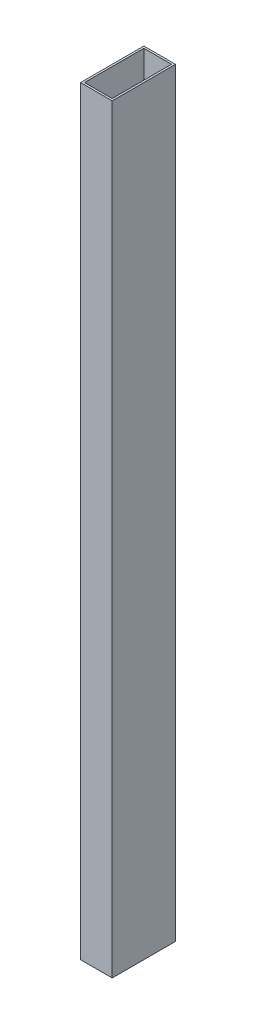
SolidWorks part; units mm, degrees
ref_plane "Front Plane" through (0, 0, 0) normal (0, 0, 1) x (1, 0, 0)
ref_plane "Top Plane" through (0, 0, 0) normal (0, 1, 0) x (1, 0, 0)
ref_plane "Right Plane" through (0, 0, 0) normal (1, 0, 0) x (0, 0, -1)
sketch "Sketch1" plane through (0, 0, 0) normal (0, 1, 0) x (1, 0, 0)
  line L1 (12.7, -25.4) -> (-12.7, -25.4)
  line L2 (12.7, -25.4) -> (12.7, 25.4)
  line L3 (12.7, 25.4) -> (-12.7, 25.4)
  line L4 (-12.7, -25.4) -> (-12.7, 25.4)
  line L5 (12.7, -25.4) -> (-12.7, 25.4) construction
  line L6 (12.7, 25.4) -> (-12.7, -25.4) construction
  line L7 (11.1125, -23.8125) -> (-11.1125, -23.8125)
  line L8 (11.1125, -23.8125) -> (11.1125, 23.8125)
  line L9 (11.1125, 23.8125) -> (-11.1125, 23.8125)
  line L10 (-11.1125, -23.8125) -> (-11.1125, 23.8125)
  line L11 (11.1125, -23.8125) -> (-11.1125, 23.8125) construction
  line L12 (11.1125, 23.8125) -> (-11.1125, -23.8125) construction
  point P0 (0, 0)
  point P6 (0, 0)
  dimension "D1" = 50.8
  dimension "D2" = 25.4
  dimension "D3" = 47.625
  dimension "D4" = 22.225
extrude "Boss-Extrude1" add sketch "Sketch1" along normal blind 609.6
